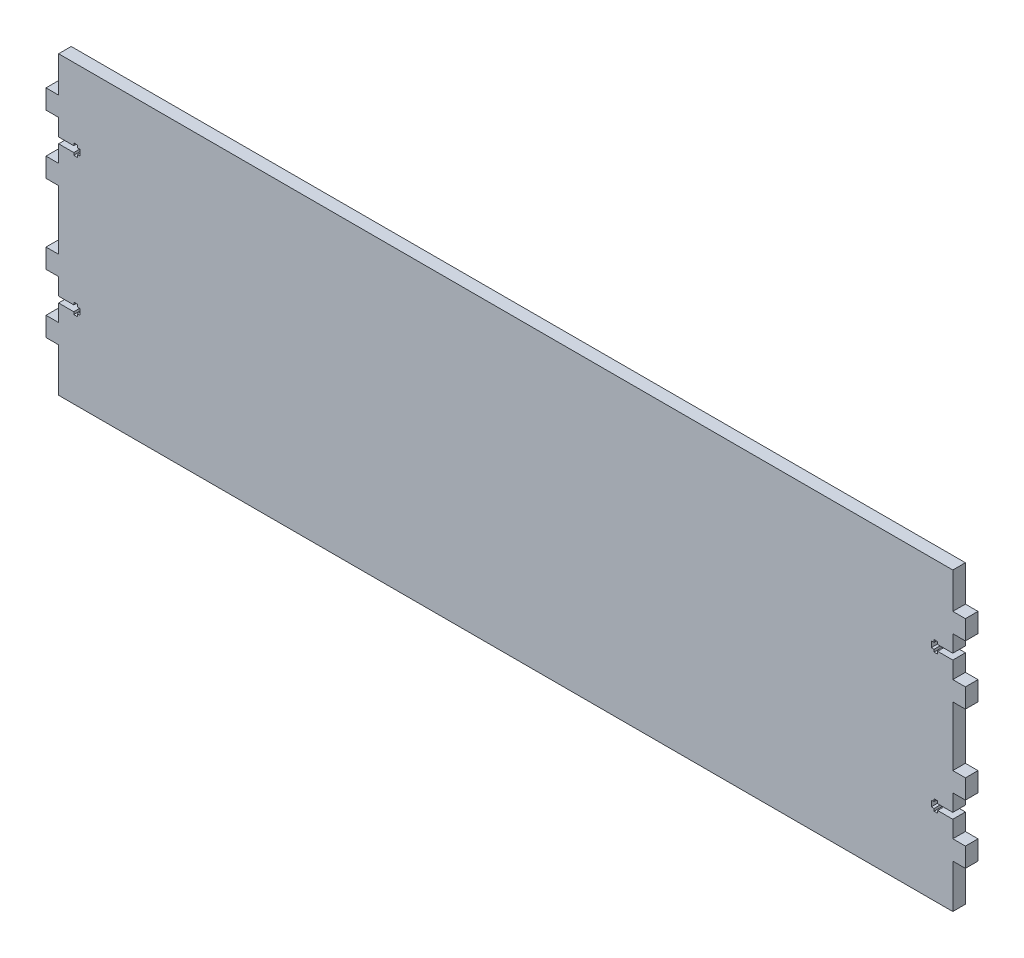
SolidWorks part; units mm, degrees
material "Acrylic (Medium-high impact)"
ref_plane "Front Plane" through (0, 0, 0) normal (0, 0, 1) x (1, 0, 0)
ref_plane "Top Plane" through (0, 0, 0) normal (0, 1, 0) x (1, 0, 0)
ref_plane "Right Plane" through (0, 0, 0) normal (1, 0, 0) x (0, 0, -1)
sketch "Sketch1" plane through (0, 0, 0) normal (0, 0, 1) x (1, 0, 0)
  line L0 (0, 146.1) -> (0, 127.9)
  line L1 (0, -4.09) -> (454, -4.09)
  line L2 (7.7, 106.4993) -> (0, 106.4993)
  line L3 (0, 146.1) -> (454, 146.1)
  line L4 (454, 36.4993) -> (454, 27.9)
  line L5 (0, 118.1) -> (0, 109.5007)
  line L6 (-6.4, 97.9) -> (-6.4, 88.1)
  line L7 (9.5, 105.2507) -> (9.5, 106.4993)
  line L8 (10.9, 106.4993) -> (9.5, 106.4993)
  line L9 (9.5, 109.5007) -> (9.5, 110.7507)
  line L10 (9.5, 110.7507) -> (7.7, 110.7507)
  line L11 (10.9, 109.5007) -> (9.5, 109.5007)
  line L12 (7.7, 109.5007) -> (0, 109.5007)
  line L13 (0, 97.9) -> (-6.4, 97.9)
  line L14 (7.7, 110.7507) -> (7.7, 109.5007)
  line L15 (-6.4, 88.1) -> (0, 88.1)
  line L16 (0, 127.9) -> (-6.4, 127.9)
  line L17 (-6.4, 127.9) -> (-6.4, 118.1)
  line L18 (7.7, 105.2507) -> (7.7, 106.4993)
  line L19 (-6.4, 118.1) -> (0, 118.1)
  line L20 (9.5, 105.2507) -> (7.7, 105.2507)
  line L21 (10.9, 109.5007) -> (10.9, 106.4993)
  line L22 (0, 106.4993) -> (0, 97.9)
  line L23 (0, 88.1) -> (0, 57.9)
  line L24 (-6.4, 18.1) -> (0, 18.1)
  line L25 (7.7, 39.5007) -> (0, 39.5007)
  line L26 (7.7, 36.4993) -> (0, 36.4993)
  line L27 (9.5, 39.5007) -> (9.5, 40.7507)
  line L28 (10.9, 39.5007) -> (9.5, 39.5007)
  line L29 (9.5, 35.2507) -> (7.7, 35.2507)
  line L30 (7.7, 35.2507) -> (7.7, 36.4993)
  line L31 (0, 27.9) -> (-6.4, 27.9)
  line L32 (10.9, 39.5007) -> (10.9, 36.4993)
  line L33 (0, 18.1) -> (0, -4.09)
  line L34 (-6.4, 27.9) -> (-6.4, 18.1)
  line L35 (227, 150) -> (227, -4.09) construction
  line L36 (-6.4, 57.9) -> (-6.4, 48.1)
  line L37 (7.7, 40.7507) -> (7.7, 39.5007)
  line L38 (0, 57.9) -> (-6.4, 57.9)
  line L39 (-6.4, 48.1) -> (0, 48.1)
  line L40 (9.5, 35.2507) -> (9.5, 36.4993)
  line L41 (10.9, 36.4993) -> (9.5, 36.4993)
  line L42 (9.5, 40.7507) -> (7.7, 40.7507)
  line L43 (0, 48.1) -> (0, 39.5007)
  line L44 (0, 36.4993) -> (0, 27.9)
  line L45 (454, 48.1) -> (454, 39.5007)
  line L46 (444.5, 40.7507) -> (446.3, 40.7507)
  line L47 (443.1, 36.4993) -> (444.5, 36.4993)
  line L48 (444.5, 35.2507) -> (444.5, 36.4993)
  line L49 (460.4, 48.1) -> (454, 48.1)
  line L50 (454, 57.9) -> (460.4, 57.9)
  line L51 (446.3, 40.7507) -> (446.3, 39.5007)
  line L52 (460.4, 57.9) -> (460.4, 48.1)
  line L53 (460.4, 27.9) -> (460.4, 18.1)
  line L54 (454, 18.1) -> (454, -4.09)
  line L55 (443.1, 39.5007) -> (443.1, 36.4993)
  line L56 (454, 27.9) -> (460.4, 27.9)
  line L57 (446.3, 35.2507) -> (446.3, 36.4993)
  line L58 (444.5, 35.2507) -> (446.3, 35.2507)
  line L59 (443.1, 39.5007) -> (444.5, 39.5007)
  line L60 (444.5, 39.5007) -> (444.5, 40.7507)
  line L61 (446.3, 36.4993) -> (454, 36.4993)
  line L62 (446.3, 39.5007) -> (454, 39.5007)
  line L63 (460.4, 18.1) -> (454, 18.1)
  line L64 (454, 88.1) -> (454, 57.9)
  line L65 (454, 106.4993) -> (454, 97.9)
  line L66 (443.1, 109.5007) -> (443.1, 106.4993)
  line L67 (444.5, 105.2507) -> (446.3, 105.2507)
  line L68 (460.4, 118.1) -> (454, 118.1)
  line L69 (446.3, 105.2507) -> (446.3, 106.4993)
  line L70 (460.4, 127.9) -> (460.4, 118.1)
  line L71 (454, 127.9) -> (460.4, 127.9)
  line L72 (460.4, 88.1) -> (454, 88.1)
  line L73 (446.3, 110.7507) -> (446.3, 109.5007)
  line L74 (454, 97.9) -> (460.4, 97.9)
  line L75 (446.3, 109.5007) -> (454, 109.5007)
  line L76 (443.1, 109.5007) -> (444.5, 109.5007)
  line L77 (444.5, 110.7507) -> (446.3, 110.7507)
  line L78 (444.5, 109.5007) -> (444.5, 110.7507)
  line L79 (443.1, 106.4993) -> (444.5, 106.4993)
  line L80 (444.5, 105.2507) -> (444.5, 106.4993)
  line L81 (460.4, 97.9) -> (460.4, 88.1)
  line L82 (454, 118.1) -> (454, 109.5007)
  line L83 (446.3, 106.4993) -> (454, 106.4993)
  line L84 (454, 146.1) -> (454, 127.9)
  dimension "D1" = 150.19
  dimension "D2" = 454
extrude "Boss-Extrude1" add sketch "Sketch1" along normal blind 6.4
